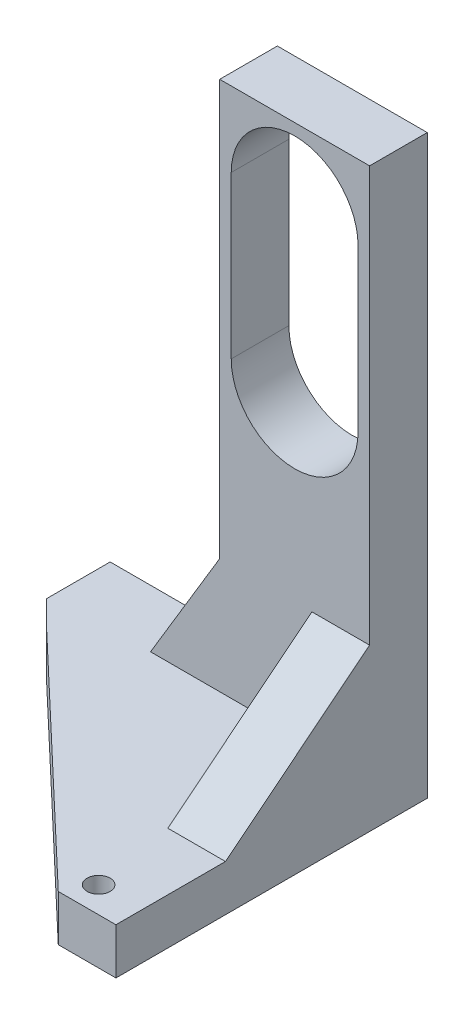
SolidWorks part; units mm, degrees
ref_plane "前视基准面" through (0, 0, 0) normal (0, 0, 1) x (1, 0, 0)
ref_plane "上视基准面" through (0, 0, 0) normal (0, 1, 0) x (1, 0, 0)
ref_plane "右视基准面" through (0, 0, 0) normal (1, 0, 0) x (0, 0, -1)
other "Configuration Table"
sketch "草图2" plane through (0, 0, 0) normal (0, 0, 1) x (1, 0, 0)
  line L0 (13, -58.75) -> (-13, -58.75)
  line L1 (-13, -58.75) -> (-13, 38.25)
  line L2 (13, -58.75) -> (13, 38.25)
  line L3 (-13, 38.25) -> (13, 38.25)
  dimension "D2" = 97
  dimension "D3" = 26
extrude "凸台-拉伸1" add sketch "草图2" along normal blind 10 contours L1 L3 L2 L0
sketch "草图3" plane through (0, 0, 0) normal (0, 0, 1) x (1, 0, 0)
  line L0 (-11, -2.75) -> (-11, 25.25)
  line L3 (11, -2.75) -> (11, 25.25)
  arc A2 (-11, -2.75) -> (11, -2.75) centre (0, -2.75) ccw
  arc A3 (-11, 25.25) -> (11, 25.25) centre (0, 25.25) cw
  point P5 (0, 17.25)
  point P7 (0, 17.25)
extrude "切除-拉伸11" cut sketch "草图3" along normal blind 10
sketch3d "3D草图1"
  point P0 (4.6572, -58.75, 5.0982)
ref_plane "基准面1" through (0, -58.75, 0) normal (0, -1, 0) x (1, 0, 0)
sketch "草图4" plane through (0, -58.75, 0) normal (0, -1, 0) x (1, 0, 0)
  line L0 (13, 0) -> (13, 54)
  line L6 (13, 0) -> (-37, 0)
  line L7 (13, 54) -> (3, 54)
  line L8 (-37, 0) -> (-37, 16)
  line L9 (-37, 16) -> (3, 54)
extrude "凸台-拉伸2" add sketch "草图4" along normal blind 3
sketch3d "3D草图2"
  point P0 (2.5198, -36.8106, 0)
ref_plane "基准面2" through (0, 0, 0) normal (0, 0, -1) x (-1, 0, 0)
sketch3d "3D草图3"
  point P0 (-15.3078, -61.75, 22.7978)
ref_plane "基准面3" through (0, -61.75, 0) normal (0, -1, 0) x (1, 0, 0)
sketch "草图7" plane through (0, -61.75, 0) normal (0, -1, 0) x (1, 0, 0)
  circle A1 centre (5.5, 49.5) radius 2
extrude "切除-拉伸12" cut sketch "草图7" against normal through all
sketch "草图9" plane through (0, -58.75, 0) normal (0, 1, 0) x (1, 0, 0)
  line L0 (-37, 0) -> (-37, -16)
  line L1 (-37, -16) -> (3, -54)
  line L2 (3, -54) -> (13, -54)
  line L3 (13, -54) -> (13, -10)
  line L4 (13, -10) -> (-13, -10)
  line L5 (-13, -10) -> (-13, 0)
  line L6 (-13, 0) -> (-37, 0)
extrude "凸台-拉伸6" add sketch "草图9" along normal blind 5
sketch "草图11" plane through (0, 0, 10) normal (0, 0, 1) x (1, 0, 0)
  line L15 (-13, -53.75) -> (-25, -53.75)
  line L16 (-37, -53.75) -> (3, -53.75) construction
  line L17 (-13, -53.75) -> (-13, -33.75)
  line L18 (-13, -53.75) -> (-13, 38.25) construction
  line L19 (-13, -33.75) -> (-25, -53.75)
sketch "草图12" plane through (13, 0, 0) normal (1, 0, 0) x (0, 0, -1)
  line L3 (-10, -53.75) -> (-35, -53.75)
  line L4 (-54, -53.75) -> (-10, -53.75) construction
  line L6 (-10, -53.75) -> (-10, -33.75)
  line L7 (-10, -53.75) -> (-10, 38.25) construction
  line L9 (-10, -33.75) -> (-35, -53.75)
extrude "凸台-拉伸8" add sketch "草图12" against normal blind 10
sketch "草图14" plane through (0, -53.75, 0) normal (0, 1, 0) x (1, 0, 0)
  line L0 (13, -54) -> (5.5, -54)
  line L1 (3, -54) -> (13, -54) construction
  line L2 (5.5, -54) -> (5.5, -49.5)
  circle A1 centre (5.5, -49.5) radius 2
extrude "切除-拉伸13" cut sketch "草图14" against normal blind 10 contours A1
extrude "凸台-拉伸9" add sketch "草图11" against normal blind 10
sketch "草图15" plane through (0, -53.75, 0) normal (0, 1, 0) x (1, 0, 0)
  line L0 (-37, 0) -> (-42, 0)
  line L1 (-37, -16) -> (-42, -11)
  line L2 (-42, -11) -> (-42, 0)
  line L3 (-37, 0) -> (-37, -16)
extrude "凸台-拉伸10" add sketch "草图15" against normal blind 8 contours L2 L0 L3 L1
